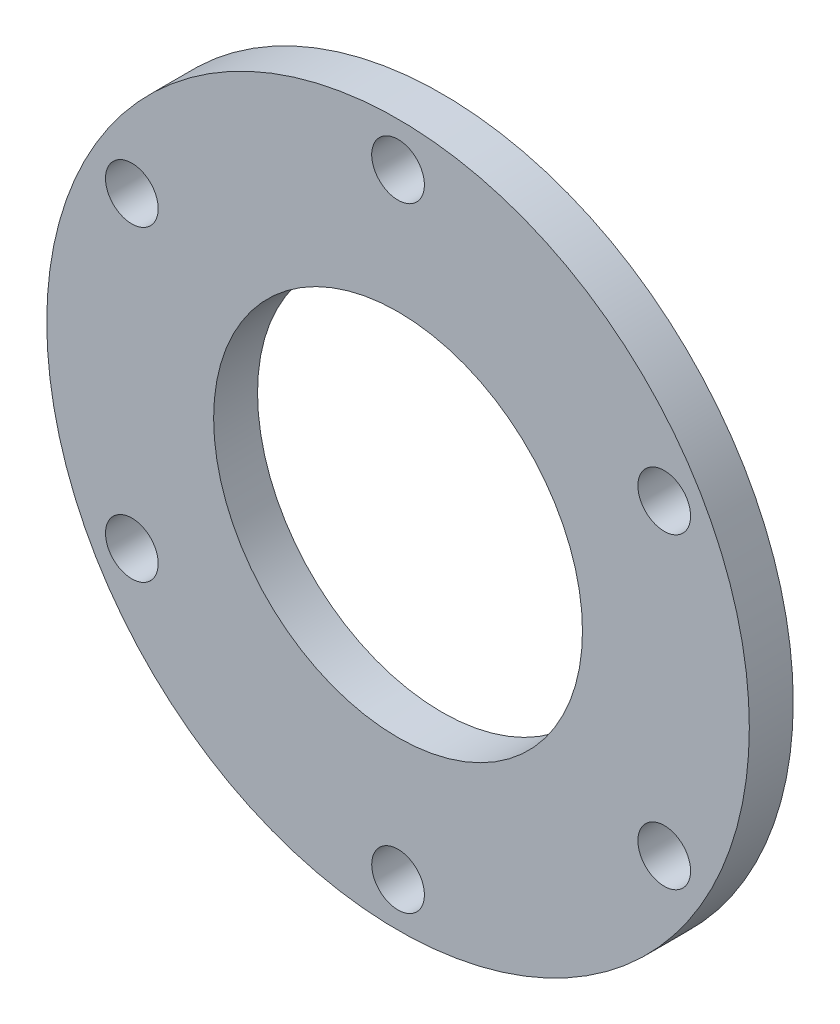
SolidWorks part; units mm, degrees
material "Plain Carbon Steel"
ref_plane "Front" through (0, 0, 0) normal (0, 0, 1) x (1, 0, 0)
ref_plane "Top" through (0, 0, 0) normal (0, 1, 0) x (1, 0, 0)
ref_plane "Right" through (0, 0, 0) normal (1, 0, 0) x (0, 0, -1)
sketch "Sketch1" plane through (0, 0, 0) normal (0, 0, 1) x (1, 0, 0)
  circle A0 centre (0, 0) radius 25.4
  circle A1 centre (0, 0) radius 13.335
  dimension "D1" = 50.8
  dimension "D2" = 26.67
extrude "Boss-Extrude1" add sketch "Sketch1" along normal blind 3.175
sketch "Sketch2" plane through (0, 0, 3.175) normal (0, 0, 1) x (1, 0, 0)
  circle A0 centre (0, 0) radius 22.225 construction
  circle A1 centre (0, 22.225) radius 1.905
  dimension "D1" = 44.45
  dimension "D2" = 3.81
extrude "Cut-Extrude1" cut sketch "Sketch2" against normal through all
pattern_circular "CirPattern1" count 6 over 360 about axis through (0, 0, 0) along (0, 0, 1) of "Cut-Extrude1"
